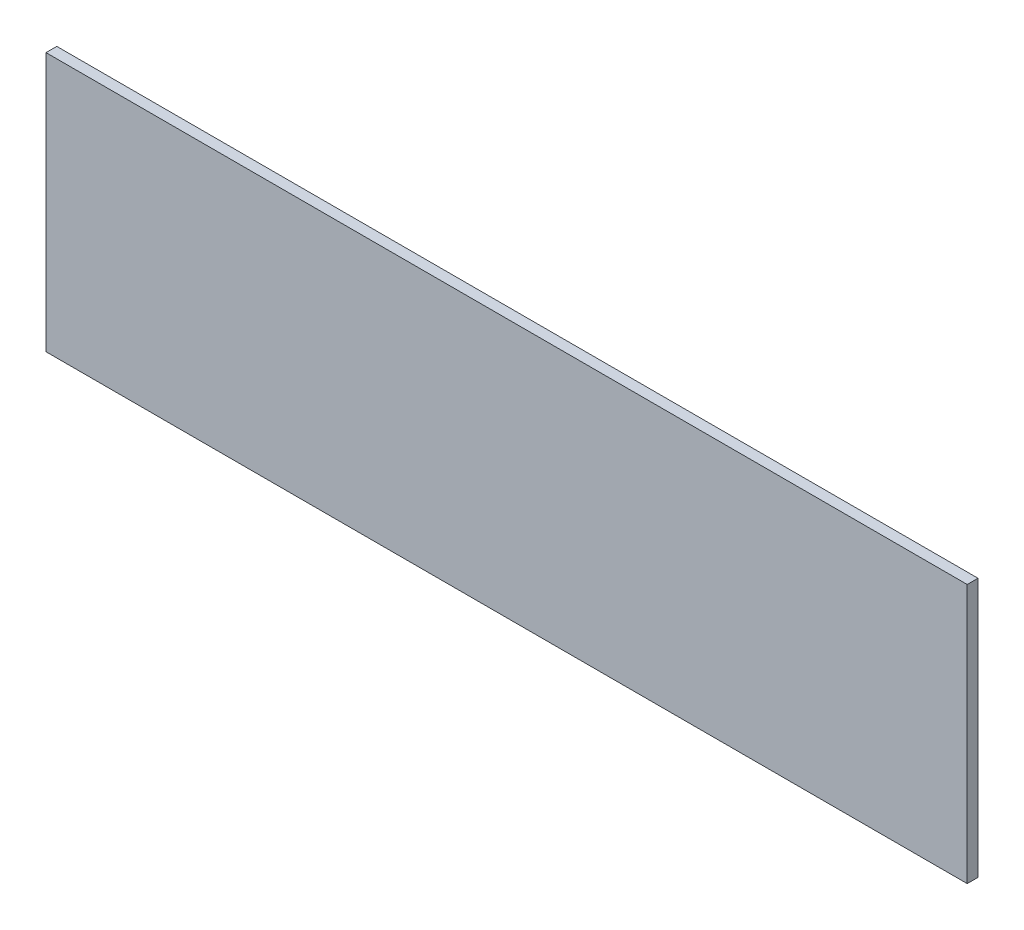
SolidWorks part; units mm, degrees
material "1060 Alloy"
ref_plane "Front Plane" through (0, 0, 0) normal (0, 0, 1) x (1, 0, 0)
ref_plane "Top Plane" through (0, 0, 0) normal (0, 1, 0) x (1, 0, 0)
ref_plane "Right Plane" through (0, 0, 0) normal (1, 0, 0) x (0, 0, -1)
sketch "Sketch1" plane through (0, 0, 0) normal (0, 0, 1) x (1, 0, 0)
  line L1 (0, 0) -> (406.4, 0)
  line L2 (0, 0) -> (0, 114.3)
  line L3 (0, 114.3) -> (406.4, 114.3)
  line L4 (406.4, 0) -> (406.4, 114.3)
extrude "Boss-Extrude1" add sketch "Sketch1" along normal blind 4.7625
